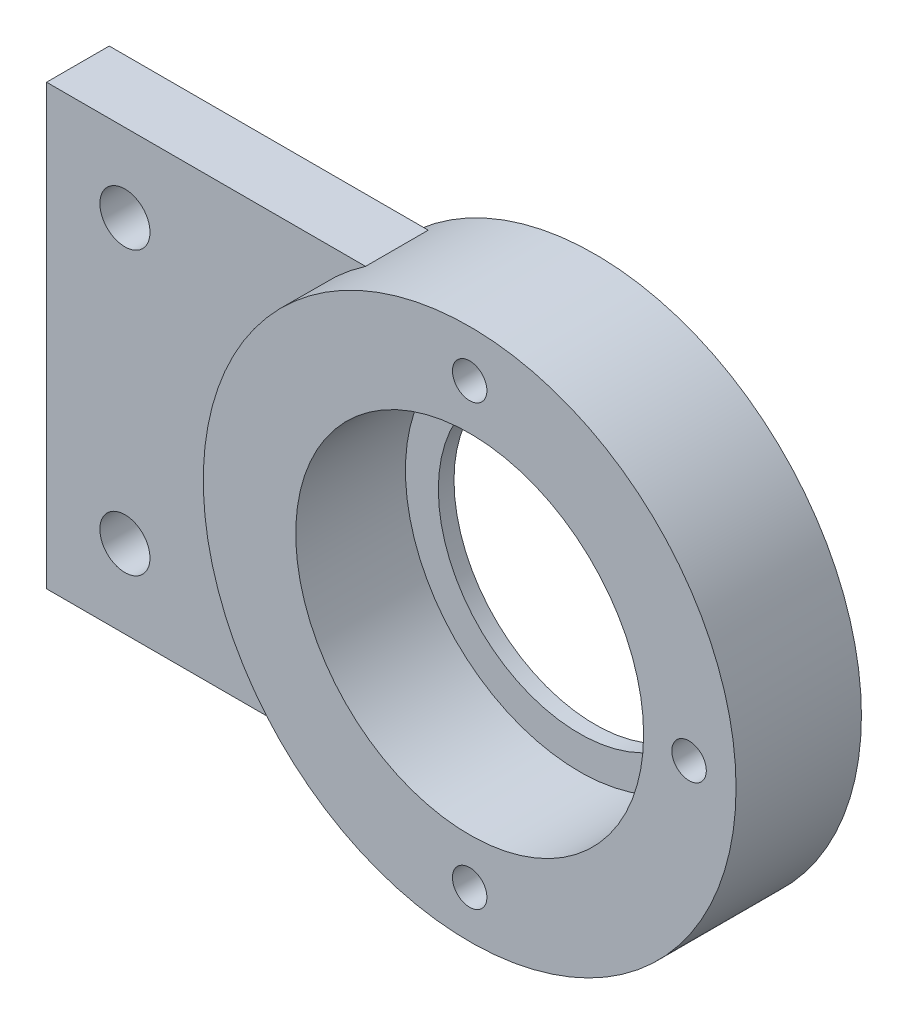
SolidWorks part; units mm, degrees
ref_plane "Front Plane" through (0, 0, 0) normal (0, 0, 1) x (1, 0, 0)
ref_plane "Top Plane" through (0, 0, 0) normal (0, 1, 0) x (1, 0, 0)
ref_plane "Right Plane" through (0, 0, 0) normal (1, 0, 0) x (0, 0, -1)
sketch "Bearing_housing_profile" plane through (0, 0, 0) normal (0, 0, 1) x (1, 0, 0)
  circle A0 centre (0, 0) radius 17
  circle A1 centre (0, 0) radius 11.1
  dimension "D1" = 34
  dimension "D2" = 22.2
extrude "Bearing_housing" add sketch "Bearing_housing_profile" along normal blind 7
sketch "Mounting_web_profile" plane through (0, 0, 0) normal (0, 0, 1) x (1, 0, 0)
  line L1 (-30, -14) -> (0, -14)
  line L2 (-30, -14) -> (-30, 14)
  line L3 (-30, 14) -> (0, 14)
  line L4 (0, -14) -> (0, 14)
  dimension "D1" = 30
  dimension "D2" = 28
extrude "Mounting_web" add sketch "Mounting_web_profile" along normal blind 4
sketch "Bearing_seat_profile" plane through (0, 0, 0) normal (0, 0, 1) x (1, 0, 0)
  circle A0 centre (0, 0) radius 11.1
  dimension "D1" = 22.2
extrude "Bearing_seat" cut sketch "Bearing_seat_profile" along normal through all from offset 50
sketch "Inner_outer_race_retaining_lip_profile" plane through (0, 0, 0) normal (0, 0, 1) x (1, 0, 0)
  circle A0 centre (0, 0) radius 17
  circle A1 centre (0, 0) radius 9
  dimension "D1" = 34
  dimension "D2" = 18
extrude "Inner_outer_race_retaining_lip" add sketch "Inner_outer_race_retaining_lip_profile" along normal blind 1 from offset 1
sketch "Standoff_fasteners_profile" plane through (0, 0, 0) normal (0, 0, 1) x (1, 0, 0)
  circle A0 centre (-25, -9) radius 1.6
  circle A1 centre (-25, 9) radius 1.6
  dimension "D1" = 3.2
  dimension "D2" = 3.2
extrude "Standoff_fasteners" cut sketch "Standoff_fasteners_profile" along normal through all from offset 50
sketch "Bearing_keeper_fasteners_profile" plane through (0, 0, 0) normal (0, 0, 1) x (1, 0, 0)
  circle A0 centre (14, 0) radius 1.1
  circle A1 centre (0, -14) radius 1.1
  circle A2 centre (0, 14) radius 1.1
  dimension "D1" = 2.2
  dimension "D2" = 2.2
  dimension "D3" = 2.2
extrude "Bearing_keeper_fasteners" cut sketch "Bearing_keeper_fasteners_profile" along normal through all from offset 50
